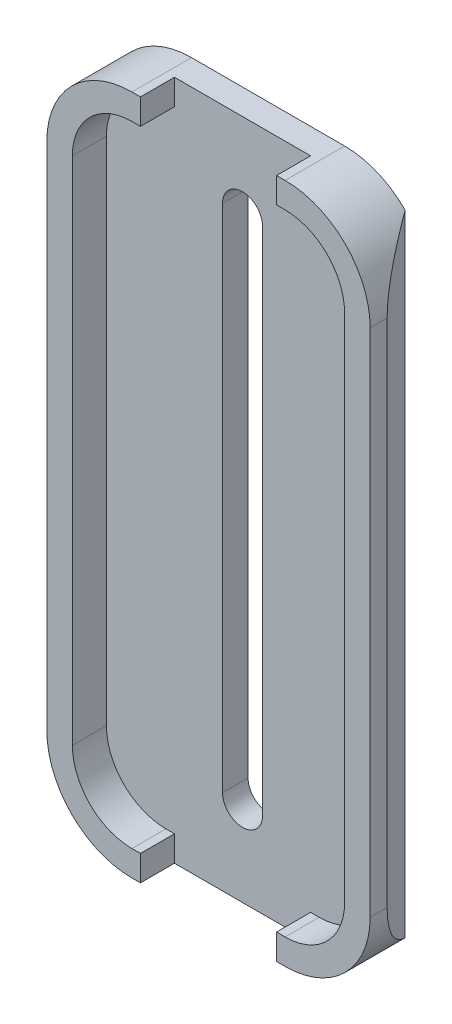
SolidWorks part; units mm, degrees
material "Сплав 2024"
ref_plane "Спереди" through (0, 0, 0) normal (0, 0, 1) x (1, 0, 0)
ref_plane "Сверху" through (0, 0, 0) normal (0, 1, 0) x (1, 0, 0)
ref_plane "Справа" through (0, 0, 0) normal (1, 0, 0) x (0, 0, -1)
sketch "Эскиз1" plane through (0, 0, 0) normal (0, 1, 0) x (1, 0, 0)
  line L0 (0, 0) -> (-38, 0)
  line L1 (-38, 0) -> (-38, 2)
  line L2 (-38, 2) -> (-35.1132, 7)
  line L3 (-35.1132, 7) -> (-2.8868, 7)
  line L4 (-2.8868, 7) -> (0, 2)
  line L5 (0, 2) -> (0, 0)
  dimension "D1" = 2
  dimension "D2" = 38
  dimension "D3" = 60
  dimension "D4" = 60
  dimension "D5" = 7
extrude "Бобышка-Вытянуть1" add sketch "Эскиз1" along normal blind 80
fillet "Скругление1" radius 10 4 edges at (0, 0, -1) (-38, 0, -1) (-38, 80, -1) (0, 80, -1)
sketch "Эскиз2" plane through (0, 0, 0) normal (0, 0, 1) x (1, 0, 0)
  line L8 (-28, 3) -> (-10, 3)
  line L9 (-3, 10) -> (-3, 70)
  line L10 (-10, 77) -> (-28, 77)
  line L11 (-35, 70) -> (-35, 10)
  line L12 (-28, 3) -> (-10, 3)
  line L13 (-3, 10) -> (-3, 70)
  line L14 (-10, 77) -> (-28, 77)
  line L15 (-35, 70) -> (-35, 10)
  arc A8 (-10, 3) -> (-3, 10) centre (-10, 10) ccw
  arc A9 (-3, 70) -> (-10, 77) centre (-10, 70) ccw
  arc A10 (-28, 77) -> (-35, 70) centre (-28, 70) ccw
  arc A11 (-35, 10) -> (-28, 3) centre (-28, 10) ccw
  arc A12 (-10, 3) -> (-3, 10) centre (-10, 10) ccw
  arc A13 (-3, 70) -> (-10, 77) centre (-10, 70) ccw
  arc A14 (-28, 77) -> (-35, 70) centre (-28, 70) ccw
  arc A15 (-35, 10) -> (-28, 3) centre (-28, 10) ccw
  dimension "D1" = 3
extrude "Вырез-Вытянуть1" cut sketch "Эскиз2" against normal offset from surface (4 mm away) 3 up to face at (-19, 40, -7)
sketch "Эскиз3" plane through (0, 0, 0) normal (0, 0, 1) x (1, 0, 0)
  line L0 (-3, 40) -> (-9.8102, 40) construction
  line L1 (-3, 70) -> (-3, 10) construction
  line L2 (-19, 80) -> (-19, 77) construction
  line L3 (-28, 80) -> (-10, 80) construction
  line L4 (-28, 77) -> (-10, 77) construction
  line L5 (-27, 3) -> (-11, 0) construction
  line L6 (-27, 80) -> (-11, 80)
  line L7 (-27, 80) -> (-27, 77)
  line L8 (-27, 77) -> (-11, 77)
  line L9 (-11, 80) -> (-11, 77)
  line L10 (-27, 80) -> (-11, 77) construction
  line L11 (-27, 77) -> (-11, 80) construction
  line L12 (-27, 0) -> (-11, 3) construction
  line L13 (-19, 0) -> (-19, 3) construction
  line L14 (-11, 0) -> (-11, 3)
  line L15 (-27, 3) -> (-11, 3)
  line L16 (-27, 0) -> (-27, 3)
  line L17 (-27, 0) -> (-11, 0)
  point P10 (-19, 78.5)
  point P21 (-19, 1.5)
  dimension "D1" = 16
extrude "Вырез-Вытянуть2" cut sketch "Эскиз3" against normal up to surface (4 mm away) up to face at (-19, 40, -4)
sketch "Эскиз4" plane through (0, 0, -7) normal (0, 0, -1) x (-1, 0, 0)
  line L0 (19, 80) -> (19, 0) construction
  line L1 (10, 80) -> (28, 80) construction
  line L2 (10, 0) -> (28, 0) construction
  line L3 (19, 70) -> (19, 10) construction
  line L4 (21.35, 70) -> (21.35, 10)
  line L5 (16.65, 70) -> (16.65, 10)
  arc A0 (21.35, 70) -> (16.65, 70) centre (19, 70) ccw
  arc A1 (16.65, 10) -> (21.35, 10) centre (19, 10) ccw
  point P8 (19, 40)
  dimension "D1" = 4.7
  dimension "D2" = 60
extrude "Вырез-Вытянуть3" cut sketch "Эскиз4" against normal up to next
sketch "Эскиз5" plane through (0, 0, -7) normal (0, 0, -1) x (-1, 0, 0)
  line L0 (19, 80) -> (19, 63.7688) construction
  line L1 (10, 80) -> (28, 80) construction
  line L2 (16.65, 40) -> (2.8868, 40) construction
  line L3 (16.65, 70) -> (16.65, 10) construction
  line L4 (2.8868, 77.0286) -> (2.8868, 2.9714) construction
  line L5 (32.2316, 5) -> (24.2316, 75) construction
  line L6 (5.7684, 75) -> (13.7684, 75)
  line L7 (5.7684, 75) -> (5.7684, 5)
  line L8 (5.7684, 5) -> (13.7684, 5)
  line L9 (13.7684, 75) -> (13.7684, 5)
  line L10 (5.7684, 75) -> (13.7684, 5) construction
  line L11 (5.7684, 5) -> (13.7684, 75) construction
  line L12 (32.2316, 75) -> (24.2316, 5) construction
  line L13 (24.2316, 75) -> (24.2316, 5)
  line L14 (32.2316, 5) -> (24.2316, 5)
  line L15 (32.2316, 75) -> (32.2316, 5)
  line L16 (32.2316, 75) -> (24.2316, 75)
  point P10 (9.7684, 40)
  point P19 (28.2316, 40)
  dimension "D1" = 8
  dimension "D2" = 70
extrude "Вырез-Вытянуть4" cut sketch "Эскиз5" against normal blind 1
fillet "Скругление2" radius 2 8 edges at (-5.7684, 5, -6.5) (-24.2316, 5, -6.5) (-13.7684, 5, -6.5) (-32.2316, 5, -6.5) (-24.2316, 75, -6.5) (-32.2316, 75, -6.5) (-13.7684, 75, -6.5) (-5.7684, 75, -6.5)
